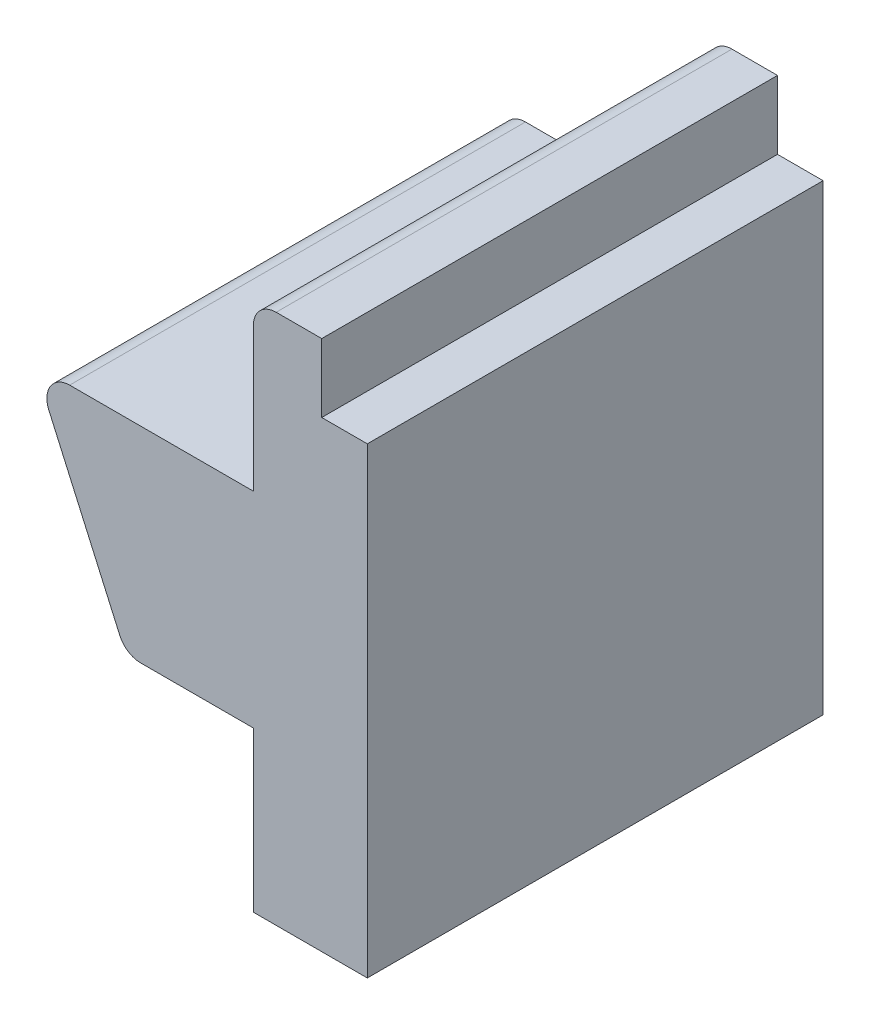
SolidWorks part; units mm, degrees
ref_plane "Plan de face" through (0, 0, 0) normal (0, 0, 1) x (1, 0, 0)
ref_plane "Plan de dessus" through (0, 0, 0) normal (0, 1, 0) x (1, 0, 0)
ref_plane "Plan de droite" through (0, 0, 0) normal (1, 0, 0) x (0, 0, -1)
sketch "Esquisse1" plane through (0, 0, 0) normal (0, 0, 1) x (1, 0, 0)
  line L4 (-2, 23.3) -> (-5, 23.3)
  line L6 (-5, 16) -> (-14.6, 16)
  line L16 (-14.6, 16) -> (-10.6, 7)
  line L24 (-10.6, 7) -> (-5, 7)
  line L25 (-5, 7) -> (-5, 0)
  line L26 (-5, 0) -> (0, 0)
  line L27 (-5, 16) -> (-5, 23.3)
  line L29 (-2, 23.3) -> (-2, 20.3)
  line L30 (-2, 20.3) -> (0, 20.3)
  line L31 (0, 20.3) -> (0, 0)
  dimension "D1" = 7
  dimension "D2" = 5.6
  dimension "D3" = 3
  dimension "D4" = 7.3
  dimension "D5" = 4
  dimension "D6" = 9
  dimension "D7" = 5
  dimension "D8" = 3
extrude "Boss.-Extru.1" add sketch "Esquisse1" along normal blind 20
fillet "Congé1" radius 1 3 edges at (-5, 23.3, 10) (-10.6, 7, 10) (-14.6, 16, 10)
sketch "Esquisse3" plane through (0, 0, 0) normal (0, -1, 0) x (1, 0, 0)
  line L0 (-5, 0) -> (0, 0) construction
  line L1 (-2.5, 4) -> (-2.5, 0) construction
  line L2 (-2.5, 16) -> (-2.5, 20) construction
  line L3 (-5, 20) -> (0, 20) construction
  circle A0 centre (-2.5, 4) radius 2
  circle A1 centre (-2.5, 16) radius 2
  point P6 (-2.5, 0)
  dimension "D1" = 4
  dimension "D2" = 4
extrude "Enlèv. mat.-Extru.1" cut sketch "Esquisse3" against normal blind 5
